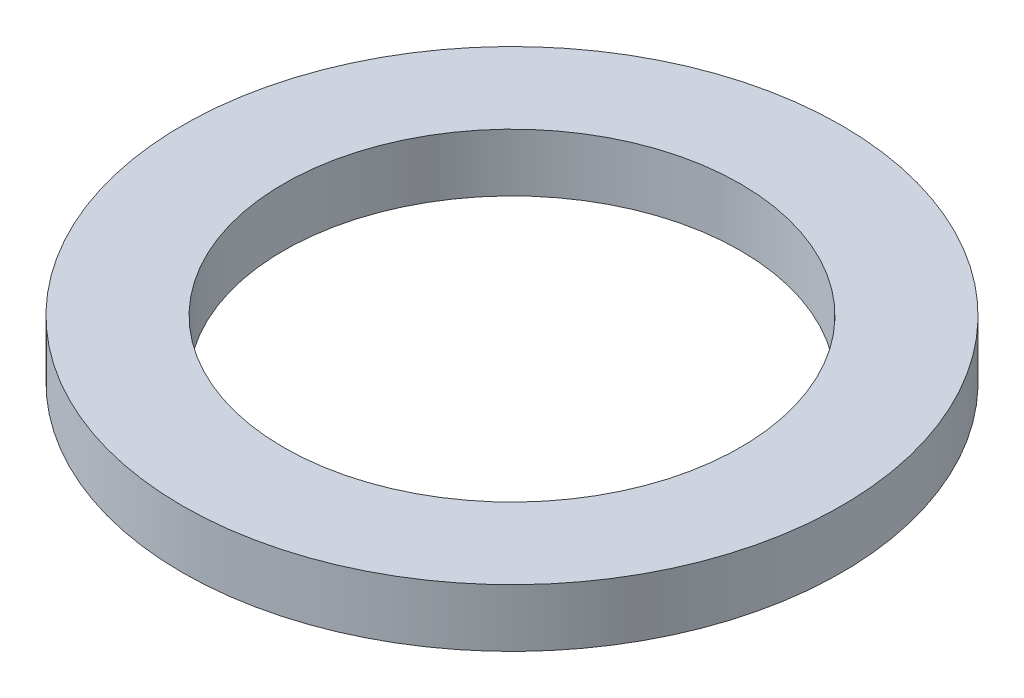
SolidWorks part; units mm, degrees
material "EPDM 60 Durometer"
ref_plane "Front Plane" through (0, 0, 0) normal (0, 0, 1) x (1, 0, 0)
ref_plane "Top Plane" through (0, 0, 0) normal (0, 1, 0) x (1, 0, 0)
ref_plane "Right Plane" through (0, 0, 0) normal (1, 0, 0) x (0, 0, -1)
sketch "Sketch2" plane through (0, 0, 0) normal (0, 1, 0) x (1, 0, 0)
  circle A0 centre (0, 0) radius 7.9
  circle A1 centre (0, 0) radius 11.4
  dimension "D1" = 3.5
  dimension "D2" = 15.8
extrude "Boss-Extrude1" add sketch "Sketch2" along normal blind 2
